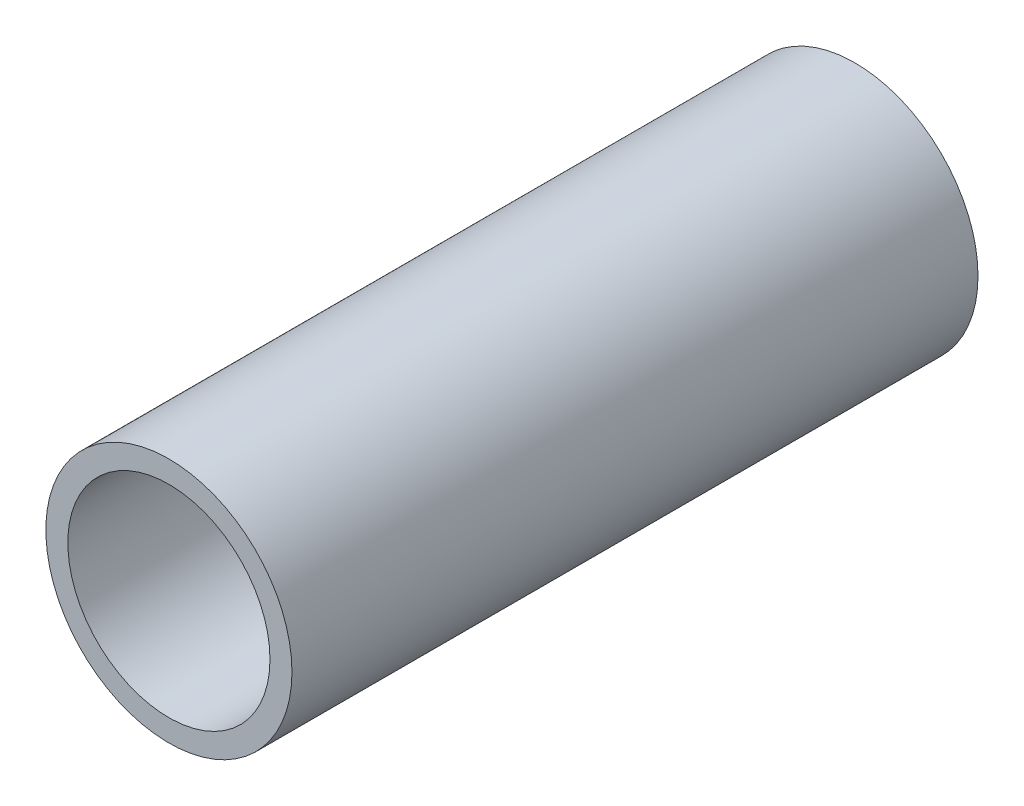
SolidWorks part; units mm, degrees
ref_plane "정면" through (0, 0, 0) normal (0, 0, 1) x (1, 0, 0)
ref_plane "윗면" through (0, 0, 0) normal (0, 1, 0) x (1, 0, 0)
ref_plane "우측면" through (0, 0, 0) normal (1, 0, 0) x (0, 0, -1)
sketch "스케치1" plane through (0, 0, 0) normal (0, 0, 1) x (1, 0, 0)
  circle A0 centre (0, 0) radius 4.6
  circle A1 centre (0, 0) radius 5.6
  dimension "D1" = 9.2
  dimension "D2" = 1
extrude "보스-돌출1" add sketch "스케치1" along normal blind 31.22
